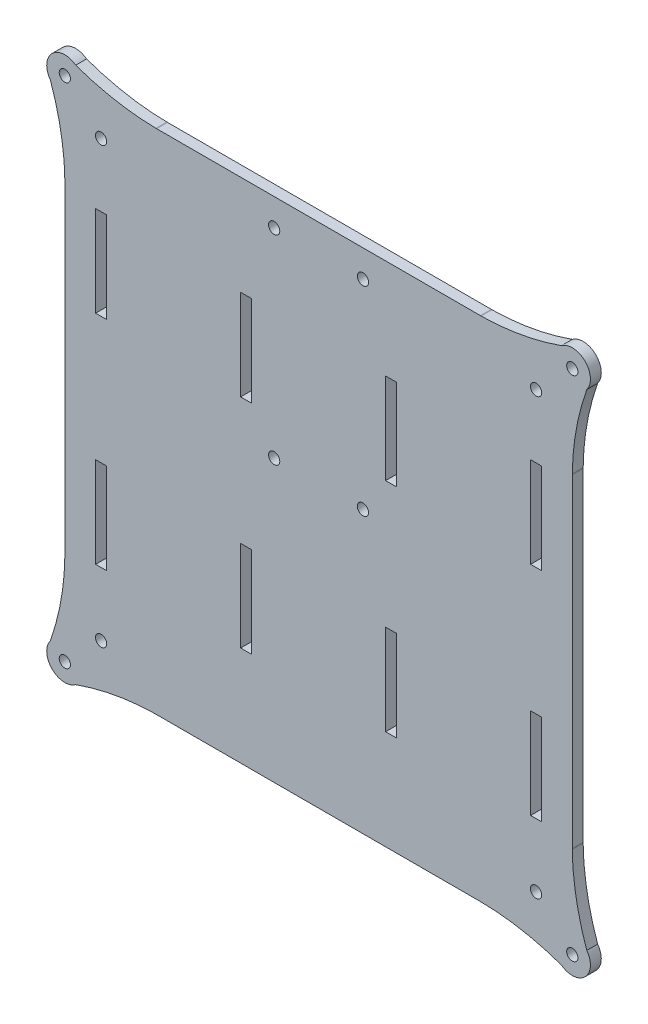
SolidWorks part; units mm, degrees
ref_plane "前基準面" through (0, 0, 0) normal (0, 0, 1) x (1, 0, 0)
ref_plane "上基準面" through (0, 0, 0) normal (0, 1, 0) x (1, 0, 0)
ref_plane "右基準面" through (0, 0, 0) normal (1, 0, 0) x (0, 0, -1)
sketch "草圖1" plane through (0, 0, 0) normal (0, 0, 1) x (1, 0, 0)
  line L1 (-70, -70) -> (70, -70)
  line L2 (-70, -70) -> (-70, 70)
  line L3 (-70, 70) -> (70, 70)
  line L4 (70, -70) -> (70, 70)
  line L5 (-70, -70) -> (70, 70) construction
  line L6 (-70, 70) -> (70, -70) construction
  line L7 (-60, -60) -> (60, -60) construction
  line L8 (-60, -60) -> (-60, 60) construction
  line L9 (-60, 60) -> (60, 60) construction
  line L10 (60, -60) -> (60, 60) construction
  line L11 (-60, -60) -> (60, 60) construction
  line L12 (-60, 60) -> (60, -60) construction
  circle A0 centre (-60, 60) radius 1.55
  circle A1 centre (60, 60) radius 1.55
  circle A2 centre (60, -60) radius 1.55
  circle A3 centre (-60, -60) radius 1.55
  point P0 (0, 0)
  point P6 (0, 0)
  dimension "D4" = 3.1
  dimension "D1" = 140
  dimension "D2" = 140
  dimension "D3" = 120
extrude "填料-伸長1" add sketch "草圖1" along normal blind 3
sketch "草圖2" plane through (0, 0, 3) normal (0, 0, 1) x (1, 0, 0)
  line L0 (-77.2505, 0) -> (82.0338, 0) construction
  line L1 (-55, 50) -> (-25, 50) construction
  line L2 (-55, 50) -> (-55, -50) construction
  line L3 (-55, -50) -> (-25, -50) construction
  line L4 (-25, 50) -> (-25, -50) construction
  line L5 (-55, 50) -> (-25, -50) construction
  line L6 (-55, -50) -> (-25, 50) construction
  line L7 (0, 57.5194) -> (0, -63.4985) construction
  line L8 (-40, 57.5194) -> (-40, -63.4985) construction
  line L9 (-60, 51.7794) -> (-60, -56.0844) construction
  line L10 (-58.5, -17.5) -> (-61.5, -17.5)
  line L11 (-58.5, 17.5) -> (-61.5, 17.5)
  line L12 (-58.5, 17.5) -> (-58.5, 42.5)
  line L13 (-58.5, 42.5) -> (-61.5, 42.5)
  line L14 (-61.5, 17.5) -> (-61.5, 42.5)
  line L15 (-58.5, 17.5) -> (-61.5, 42.5) construction
  line L16 (-58.5, 42.5) -> (-61.5, 17.5) construction
  line L17 (-61.5, -17.5) -> (-61.5, -42.5)
  line L18 (-58.5, -17.5) -> (-58.5, -42.5)
  line L19 (-58.5, -42.5) -> (-61.5, -42.5)
  line L20 (-21.5, -17.5) -> (-18.5, -17.5)
  line L21 (-21.5, -42.5) -> (-18.5, -42.5)
  line L22 (-21.5, -17.5) -> (-21.5, -42.5)
  line L23 (-18.5, -17.5) -> (-18.5, -42.5)
  line L24 (-21.5, 42.5) -> (-18.5, 42.5)
  line L25 (-21.5, 17.5) -> (-18.5, 17.5)
  line L26 (-21.5, 17.5) -> (-21.5, 42.5)
  line L27 (-18.5, 17.5) -> (-18.5, 42.5)
  line L28 (21.5, 42.5) -> (18.5, 42.5)
  line L29 (21.5, 17.5) -> (18.5, 17.5)
  line L30 (21.5, 17.5) -> (21.5, 42.5)
  line L31 (18.5, 17.5) -> (18.5, 42.5)
  line L32 (21.5, -42.5) -> (18.5, -42.5)
  line L33 (18.5, -17.5) -> (18.5, -42.5)
  line L34 (21.5, -17.5) -> (18.5, -17.5)
  line L35 (21.5, -17.5) -> (21.5, -42.5)
  line L36 (58.5, -42.5) -> (61.5, -42.5)
  line L37 (58.5, -17.5) -> (61.5, -17.5)
  line L38 (61.5, -17.5) -> (61.5, -42.5)
  line L39 (58.5, -17.5) -> (58.5, -42.5)
  line L40 (58.5, 42.5) -> (61.5, 42.5)
  line L41 (58.5, 17.5) -> (61.5, 17.5)
  line L42 (58.5, 17.5) -> (58.5, 42.5)
  line L43 (61.5, 17.5) -> (61.5, 42.5)
  line L45 (-12.25, 62.5) -> (12.25, 62.5) construction
  line L46 (-12.25, 62.5) -> (-12.25, 7.5) construction
  line L47 (-12.25, 7.5) -> (12.25, 7.5) construction
  line L48 (12.25, 62.5) -> (12.25, 7.5) construction
  line L49 (-12.25, 62.5) -> (12.25, 7.5) construction
  line L50 (-12.25, 7.5) -> (12.25, 62.5) construction
  circle A0 centre (-12.25, 62.5) radius 1.55
  circle A1 centre (12.25, 62.5) radius 1.55
  circle A2 centre (-12.25, 7.5) radius 1.55
  circle A3 centre (12.25, 7.5) radius 1.55
  point P0 (-40, 0)
  point P14 (-60, 30)
  point P47 (0, 35)
  dimension "D11" = 3.1
  dimension "D1" = 30
  dimension "D2" = 100
  dimension "D3" = 40
  dimension "D4" = 5
  dimension "D5" = 30
  dimension "D6" = 25
  dimension "D7" = 3
  dimension "D8" = 24.5
  dimension "D9" = 55
  dimension "D10" = 35
extrude "除料-伸長1" cut sketch "草圖2" against normal through all
sketch "草圖3" plane through (0, 0, 3) normal (0, 0, 1) x (1, 0, 0)
  line L0 (-79.3934, 100.6066) -> (-48.7868, 70)
  line L1 (-90, -90) -> (90, -90) construction
  line L2 (-90, -90) -> (-90, 90) construction
  line L3 (-90, 90) -> (90, 90) construction
  line L4 (90, -90) -> (90, 90) construction
  line L5 (-90, -90) -> (90, 90) construction
  line L6 (-90, 90) -> (90, -90) construction
  line L7 (70, 70) -> (-70, 70) construction
  line L8 (-100.6066, 79.3934) -> (-70, 48.7868)
  line L9 (-48.7868, 70) -> (-70, 70)
  line L10 (-70, 70) -> (-70, 48.7868)
  line L11 (0, 103.8199) -> (0, 0) construction
  line L12 (0, 0) -> (-105.1877, 0) construction
  line L13 (48.7868, 70) -> (70, 70)
  line L14 (70, 70) -> (70, 48.7868)
  line L15 (100.6066, 79.3934) -> (70, 48.7868)
  line L16 (79.3934, 100.6066) -> (48.7868, 70)
  line L17 (-48.7868, -70) -> (-70, -70)
  line L18 (-70, -70) -> (-70, -48.7868)
  line L19 (-100.6066, -79.3934) -> (-70, -48.7868)
  line L20 (-79.3934, -100.6066) -> (-48.7868, -70)
  line L21 (79.3934, -100.6066) -> (48.7868, -70)
  line L22 (48.7868, -70) -> (70, -70)
  line L23 (70, -70) -> (70, -48.7868)
  line L24 (100.6066, -79.3934) -> (70, -48.7868)
  circle A0 centre (-90, 90) radius 3
  circle A1 centre (-81, 90) radius 1.55
  circle A2 centre (-90, 98) radius 1.55
  circle A3 centre (-99, 90) radius 1.55
  circle A4 centre (-90, 82) radius 1.55
  arc A5 (-79.3934, 100.6066) -> (-100.6066, 79.3934) centre (-90, 90) ccw
  circle A6 centre (81, 90) radius 1.55
  circle A7 centre (90, 90) radius 3
  circle A8 centre (90, 82) radius 1.55
  circle A9 centre (90, 98) radius 1.55
  circle A10 centre (99, 90) radius 1.55
  arc A11 (79.3934, 100.6066) -> (100.6066, 79.3934) centre (90, 90) cw
  circle A12 centre (-90, -82) radius 1.55
  circle A13 centre (-90, -90) radius 3
  circle A14 centre (-81, -90) radius 1.55
  circle A15 centre (-90, -98) radius 1.55
  circle A16 centre (-99, -90) radius 1.55
  arc A17 (-79.3934, -100.6066) -> (-100.6066, -79.3934) centre (-90, -90) cw
  circle A18 centre (90, -82) radius 1.55
  circle A19 centre (90, -90) radius 3
  circle A20 centre (81, -90) radius 1.55
  circle A21 centre (90, -98) radius 1.55
  circle A22 centre (99, -90) radius 1.55
  arc A23 (79.3934, -100.6066) -> (100.6066, -79.3934) centre (90, -90) ccw
  point P0 (0, 0)
  dimension "D3" = 6
  dimension "D4" = 3.1
  dimension "D5" = 3.1
  dimension "D7" = 9
  dimension "D8" = 30
  dimension "D1" = 180
  dimension "D2" = 180
  dimension "D6" = 8
extrude "填料-伸長2" add sketch "草圖3" against normal blind 3
fillet "圓角1" radius 10 8 edges at (-70, -48.7868, 1.5) (48.7868, -70, 1.5) (-48.7868, -70, 1.5) (70, -48.7868, 1.5) (70, 48.7868, 1.5) (48.7868, 70, 1.5) (-48.7868, 70, 1.5) (-70, 48.7868, 1.5)
sketch "草圖7" plane through (0, 0, 3) normal (0, 0, 1) x (1, 0, 0)
  line L0 (-44.6447, 70) -> (-70, 70) construction
  line L1 (-70, 70) -> (-70, 44.6447) construction
  line L3 (0, 0) -> (-77.4699, 77.4699) construction
  line L4 (0, 0) -> (104.4183, 104.4183) construction
  line L5 (0, 0) -> (0, 77.4699) construction
  line L6 (0, 77.4699) -> (0, 0) construction
  line L7 (0, 0) -> (-88.7671, 0) construction
  line L8 (-44.6447, 70) -> (44.6447, 70)
  line L9 (70, 44.6447) -> (70, -44.6447)
  line L10 (44.6447, -70) -> (-44.6447, -70)
  line L11 (-70, -44.6447) -> (-70, 44.6447)
  line L13 (-126.0765, -125.8409) -> (126.0765, -125.8409)
  line L14 (-126.0765, -125.8409) -> (-126.0765, 125.8409)
  line L15 (-126.0765, 125.8409) -> (126.0765, 125.8409)
  line L16 (126.0765, -125.8409) -> (126.0765, 125.8409)
  line L17 (-126.0765, -125.8409) -> (126.0765, 125.8409) construction
  line L18 (-126.0765, 125.8409) -> (126.0765, -125.8409) construction
  arc A1 (-67.0045, 74.0034) -> (-74.0034, 67.0045) centre (-70, 70) ccw
  arc A2 (67.0045, 74.0034) -> (74.0034, 67.0045) centre (70, 70) cw
  arc A3 (67.0045, -74.0034) -> (74.0034, -67.0045) centre (70, -70) ccw
  arc A4 (-67.0045, -74.0034) -> (-74.0034, -67.0045) centre (-70, -70) cw
  spline S0 degree 2 poles (-67.0045, 74.0034) (-55.9925, 70.1116) (-44.6447, 70) knots 0 0 0 0.944247 0.944247 0.944247
  spline S1 degree 2 poles (-74.0034, 67.0045) (-70.1116, 55.9925) (-70, 44.6447) knots 0 0 0 0.944247 0.944247 0.944247
  spline S2 degree 2 poles (67.0045, 74.0034) (55.9925, 70.1116) (44.6447, 70) knots 0 0 0 0.944247 0.944247 0.944247
  spline S3 degree 2 poles (74.0034, 67.0045) (70.1116, 55.9925) (70, 44.6447) knots 0 0 0 0.944247 0.944247 0.944247
  spline S4 degree 2 poles (74.0034, -67.0045) (70.1116, -55.9925) (70, -44.6447) knots 0 0 0 0.944247 0.944247 0.944247
  spline S5 degree 2 poles (67.0045, -74.0034) (55.9925, -70.1116) (44.6447, -70) knots 0 0 0 0.944247 0.944247 0.944247
  spline S6 degree 2 poles (-67.0045, -74.0034) (-55.9925, -70.1116) (-44.6447, -70) knots 0 0 0 0.944247 0.944247 0.944247
  spline S7 degree 2 poles (-74.0034, -67.0045) (-70.1116, -55.9925) (-70, -44.6447) knots 0 0 0 0.944247 0.944247 0.944247
  dimension "D2" = 10
extrude "除料-伸長3" cut sketch "草圖7" against normal blind 3
sketch "草圖8" plane through (0, 0, 3) normal (0, 0, 1) x (1, 0, 0)
  line L0 (-44.6447, 70) -> (-70, 70) construction
  line L1 (-70, 70) -> (-70.0007, 44.7599) construction
  line L3 (70, -70) -> (-70, -70) construction
  line L4 (70, -70) -> (70, 70) construction
  line L5 (70, 70) -> (-70, 70) construction
  line L6 (-70, -70) -> (-70, 70) construction
  line L7 (70, -70) -> (-70, 70) construction
  line L8 (70, 70) -> (-70, -70) construction
  arc A0 (-70, 44.6447) -> (-70.0027, 44.8752) centre (-80, 44.6447) ccw construction
  circle A1 centre (-70, 70) radius 1.55
  circle A2 centre (70, 70) radius 1.55
  circle A3 centre (70, -70) radius 1.55
  circle A4 centre (-70, -70) radius 1.55
  point P7 (0, 0)
  dimension "D1" = 3.1
extrude "除料-伸長4" cut sketch "草圖8" against normal blind 3
